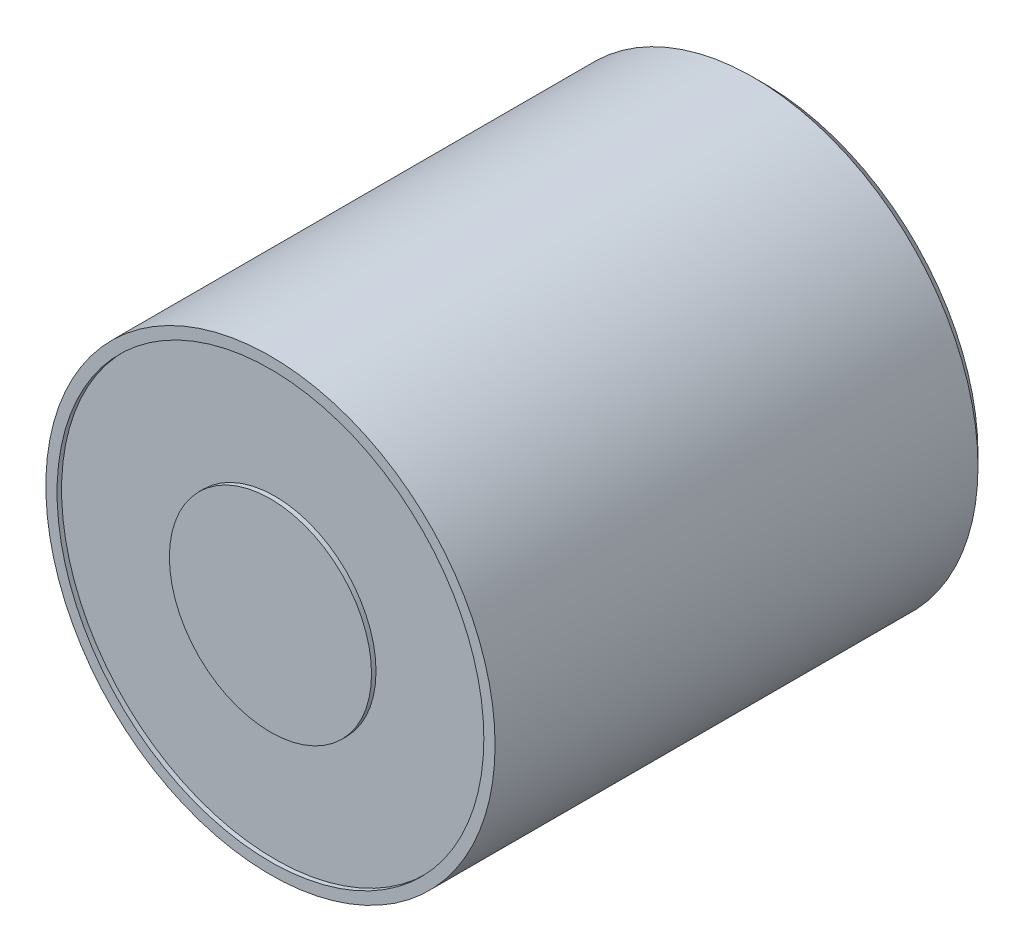
SolidWorks part; units mm, degrees
ref_plane "Front" through (0, 0, 0) normal (0, 0, 1) x (1, 0, 0)
ref_plane "Top" through (0, 0, 0) normal (0, 1, 0) x (1, 0, 0)
ref_plane "Right" through (0, 0, 0) normal (1, 0, 0) x (0, 0, -1)
sketch "Sketch1" plane through (0, 0, 0) normal (0, 0, 1) x (1, 0, 0)
  circle A0 centre (0, 0) radius 10
extrude "Boss-Extrude1" add sketch "Sketch1" along normal blind 22
sketch "Sketch2" plane through (0, 0, 22) normal (0, 0, 1) x (1, 0, 0)
  circle A0 centre (0, 0) radius 4.5
  circle A1 centre (0, 0) radius 9.5
extrude "Cut-Extrude1" cut sketch "Sketch2" against normal blind 0.2
hole_wizard "M4 Tapped Hole1" positions "Sketch5" profile "Sketch4" tap size "M4" standard "ISO"
sketch "Sketch5" plane through (0, 0, 0) normal (0, 0, -1) x (-1, 0, 0)
  point P0 (0, 0)
sketch "Sketch4" plane through (0, 0, 0) normal (1, 0, 0) x (0, 1, 0)
  line L0 (0, 0) -> (0, 5.9914)
  line L1 (0, 5.9914) -> (1.65, 5)
  line L2 (1.65, 5) -> (1.65, 0)
  line L5 (1.65, 0) -> (0, 0)
  line L10 (0, 5.9914) -> (-1.65, 5) construction
  line L11 (0, -6.35) -> (0, 107.95) construction
  dimension "Tap Drill Dia." = 3.3
  dimension "Tap Drill Depth" = 5
  dimension "Drill Angle" = 118
cosmetic thread "Hole Thread1" parameters "D1"=5, "D2"=4
chamfer "Chamfer2" distance 0.5 angle 45 1 edges at (10, 0, 0)
